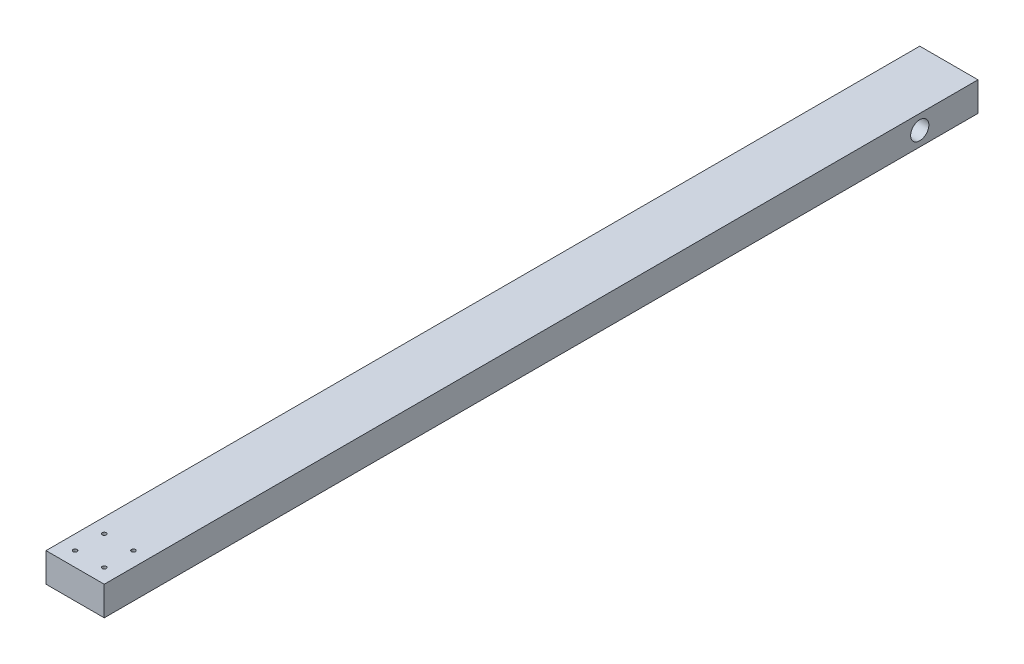
SolidWorks part; units mm, degrees
ref_plane "Front Plane" through (0, 0, 0) normal (0, 0, 1) x (1, 0, 0)
ref_plane "Top Plane" through (0, 0, 0) normal (0, 1, 0) x (1, 0, 0)
ref_plane "Right Plane" through (0, 0, 0) normal (1, 0, 0) x (0, 0, -1)
sketch "Sketch1" plane through (0, 0, 0) normal (0, 0, 1) x (1, 0, 0)
  line L1 (-50.8, 25.4) -> (50.8, 25.4)
  line L2 (-50.8, 25.4) -> (-50.8, -25.4)
  line L3 (-50.8, -25.4) -> (50.8, -25.4)
  line L4 (50.8, 25.4) -> (50.8, -25.4)
  line L5 (-50.8, 25.4) -> (50.8, -25.4) construction
  line L6 (-50.8, -25.4) -> (50.8, 25.4) construction
  point P0 (0, 0)
  dimension "D1" = 50.8
  dimension "D2" = 101.6
extrude "Boss-Extrude1" add sketch "Sketch1" along normal blind 1524
sketch "Sketch2" plane through (0, 25.4, 0) normal (0, 1, 0) x (1, 0, 0)
  line L0 (50.8, -1524) -> (-50.8, -1524) construction
  line L1 (-25.4, -1447.8) -> (25.4, -1447.8) construction
  line L2 (-25.4, -1447.8) -> (-25.4, -1498.6) construction
  line L3 (-25.4, -1498.6) -> (25.4, -1498.6) construction
  line L4 (25.4, -1447.8) -> (25.4, -1498.6) construction
  line L5 (-25.4, -1447.8) -> (25.4, -1498.6) construction
  line L6 (-25.4, -1498.6) -> (25.4, -1447.8) construction
  circle A0 centre (-25.4, -1447.8) radius 3.4925
  circle A1 centre (25.4, -1447.8) radius 3.4925
  circle A2 centre (25.4, -1498.6) radius 3.4925
  circle A3 centre (-25.4, -1498.6) radius 3.4925
  point P0 (0, -1473.2)
  dimension "D4" = 6.985
  dimension "D1" = 50.8
  dimension "D2" = 50.8
  dimension "D3" = 25.4
extrude "Cut-Extrude1" cut sketch "Sketch2" against normal up to surface (50.8 mm away) up to face at (0, -25.4, 762)
sketch "Sketch3" plane through (50.8, 0, 0) normal (1, 0, 0) x (0, 0, -1)
  line L0 (0, -25.4) -> (0, 25.4) construction
  circle A0 centre (-101.6, 0) radius 15.875
  dimension "D2" = 31.75
  dimension "D1" = 101.6
extrude "Cut-Extrude2" cut sketch "Sketch3" against normal up to surface (101.6 mm away) up to face at (-50.8, 0, 762)
